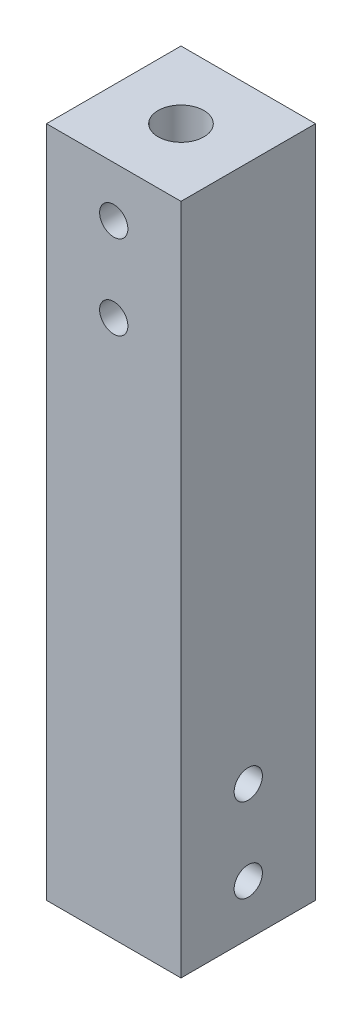
SolidWorks part; units mm, degrees
ref_plane "Front" through (0, 0, 0) normal (0, 0, 1) x (1, 0, 0)
ref_plane "Top" through (0, 0, 0) normal (0, 1, 0) x (1, 0, 0)
ref_plane "Right" through (0, 0, 0) normal (1, 0, 0) x (0, 0, -1)
sketch "Sketch1" plane through (0, 0, 0) normal (0, 1, 0) x (1, 0, 0)
  line L1 (0, 0) -> (20, 0)
  line L2 (0, 0) -> (0, 20)
  line L3 (0, 20) -> (20, 20)
  line L4 (20, 0) -> (20, 20)
  dimension "D1" = 20
  dimension "D2" = 20
extrude "Boss-Extrude1" add sketch "Sketch1" along normal blind 100
hole_wizard "M8 Tapped Hole1" positions "Sketch4" profile "Sketch5" tap size "M8" standard "ISO"
sketch "Sketch4" plane through (0, 100, 0) normal (0, 1, 0) x (1, 0, 0)
  line L0 (0, 20) -> (20, 0) construction
  line L2 (0, 0) -> (20, 20) construction
  point P13 (10, 10)
sketch "Sketch5" plane through (10, 100, -10) normal (1, 0, 0) x (0, 0, 1)
  line L0 (0, 0) -> (0, 15.7929)
  line L1 (0, 15.7929) -> (3.4, 13.75)
  line L2 (3.4, 13.75) -> (3.4, 0)
  line L5 (3.4, 0) -> (0, 0)
  line L10 (0, 15.7929) -> (-3.4, 13.75) construction
  line L11 (0, -6.35) -> (0, 107.95) construction
  dimension "Tap Drill Dia." = 6.8
  dimension "Tap Drill Depth" = 13.75
  dimension "Drill Angle" = 118
cosmetic thread "Hole Thread1"
ref_plane "Plane1" through (0, 50, 0) normal (0, 1, 0) x (1, 0, 0)
mirror "Mirror1" about plane through (0, 50, 0) normal (0, 1, 0) of "M8 Tapped Hole1"
cosmetic thread "Hole Thread2" parameters "D1"=16, "D2"=8
hole_wizard "M5 Tapped Hole1" positions "Sketch6" profile "Sketch7" tap size "M5" standard "ISO"
sketch "Sketch6" plane through (0, 0, 0) normal (0, 0, 1) x (1, 0, 0)
  line L0 (10, 100) -> (10, 95.0401) construction
  line L1 (0, 100) -> (20, 100) construction
  point P0 (10, 80)
  point P7 (10, 92.5)
  dimension "D1" = 20
  dimension "D2" = 12.5
sketch "Sketch7" plane through (10, 80, 0) normal (1, 0, 0) x (0, -1, 0)
  line L0 (0, 0) -> (0, 13.6618)
  line L1 (0, 13.6618) -> (2.1, 12.4)
  line L2 (2.1, 12.4) -> (2.1, 0)
  line L5 (2.1, 0) -> (0, 0)
  line L10 (0, 13.6618) -> (-2.1, 12.4) construction
  line L11 (0, -6.35) -> (0, 107.95) construction
  dimension "Tap Drill Dia." = 4.2
  dimension "Tap Drill Depth" = 12.4
  dimension "Drill Angle" = 118
cosmetic thread "Hole Thread3"
cosmetic thread "Hole Thread5"
hole_wizard "M5 Tapped Hole2" positions "Sketch8" profile "Sketch9" tap size "M5" standard "ISO"
sketch "Sketch8" plane through (20, 0, 0) normal (1, 0, 0) x (0, 0, -1)
  line L0 (10, 0) -> (10, 26.2195) construction
  line L1 (0, 0) -> (20, 0) construction
  point P7 (10, 20)
  point P8 (10, 7.5)
  dimension "D1" = 20
  dimension "D2" = 12.5
sketch "Sketch9" plane through (20, 7.5, -10) normal (0, 1, 0) x (0, 0, -1)
  line L0 (0, 0) -> (0, 13.6618)
  line L1 (0, 13.6618) -> (2.1, 12.4)
  line L2 (2.1, 12.4) -> (2.1, 0)
  line L5 (2.1, 0) -> (0, 0)
  line L10 (0, 13.6618) -> (-2.1, 12.4) construction
  line L11 (0, -6.35) -> (0, 107.95) construction
  dimension "Tap Drill Dia." = 4.2
  dimension "Tap Drill Depth" = 12.4
  dimension "Drill Angle" = 118
cosmetic thread "Hole Thread4"
cosmetic thread "Hole Thread6"
